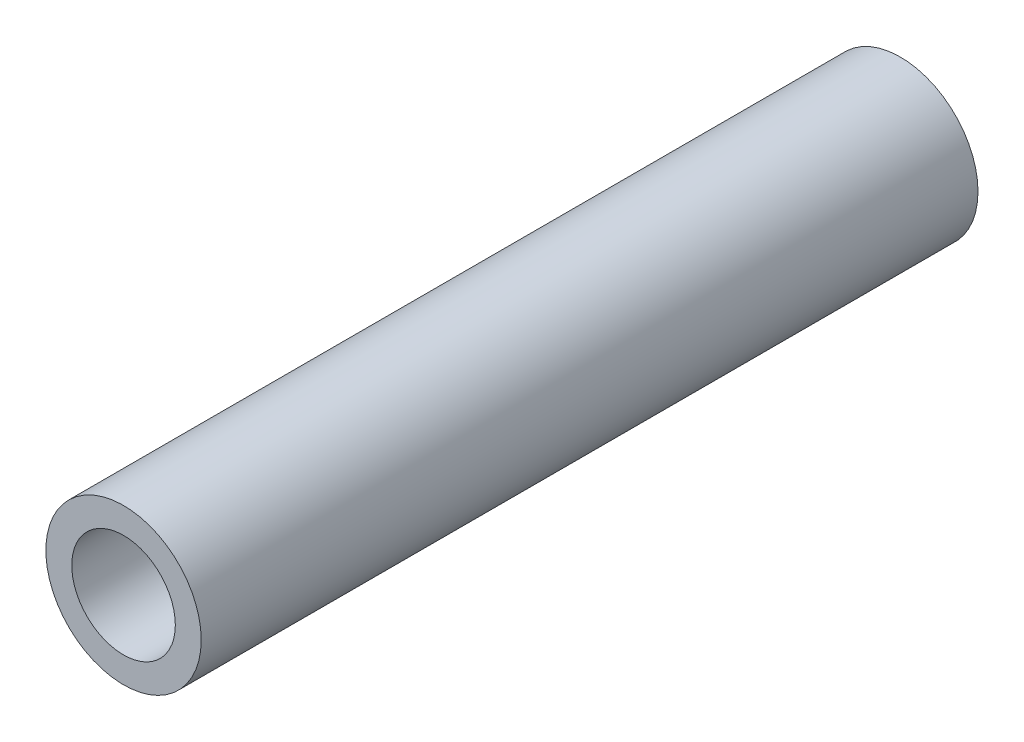
SolidWorks part; units mm, degrees
material "炭素鋼(普通)"
ref_plane "正面" through (0, 0, 0) normal (0, 0, 1) x (1, 0, 0)
ref_plane "平面" through (0, 0, 0) normal (0, 1, 0) x (1, 0, 0)
ref_plane "右側面" through (0, 0, 0) normal (1, 0, 0) x (0, 0, -1)
sketch "ｽｹｯﾁ1" plane through (0, 0, 0) normal (0, 0, 1) x (1, 0, 0)
  circle A0 centre (0, 0) radius 2
  circle A1 centre (0, 0) radius 3
  dimension "D1" = 6
  dimension "D2" = 4
extrude "ﾎﾞｽ - 押し出し1" add sketch "ｽｹｯﾁ1" along normal blind 30
